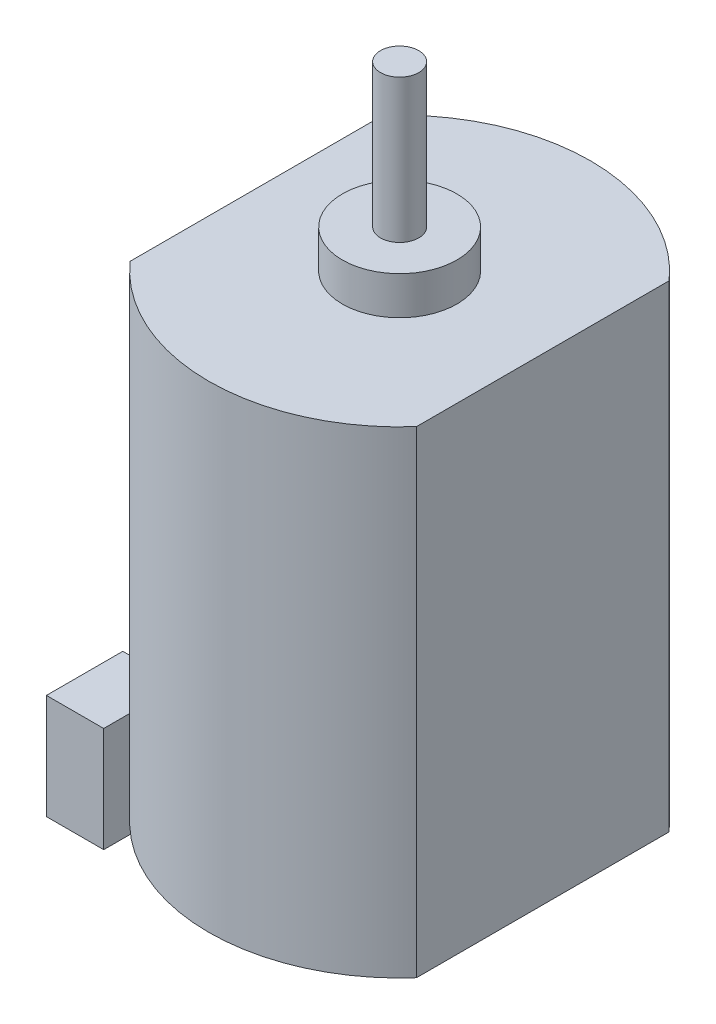
SolidWorks part; units mm, degrees
ref_plane "前视基准面" through (0, 0, 0) normal (0, 0, 1) x (1, 0, 0)
ref_plane "上视基准面" through (0, 0, 0) normal (0, 1, 0) x (1, 0, 0)
ref_plane "右视基准面" through (0, 0, 0) normal (1, 0, 0) x (0, 0, -1)
sketch "草图1" plane through (0, 0, 0) normal (0, 1, 0) x (1, 0, 0)
  circle A0 centre (0, 0) radius 10
  dimension "D1" = 20
extrude "圆柱凸台-拉伸1" add sketch "草图1" along normal blind 25
sketch "草图2" plane through (0, 0, 0) normal (0, -1, 0) x (1, 0, 0)
  line L0 (0, 0) -> (0, 8.2637) construction
  line L2 (-7.5, 10) -> (-7.5, -10)
  line L4 (7.5, 10) -> (7.5, -10)
  line L5 (7.5, 10) -> (10, 10)
  line L6 (-10, 10) -> (-7.5, 10)
  line L7 (-10, 10) -> (-10, -10)
  line L8 (-10, -10) -> (-7.5, -10)
  line L9 (10, 10) -> (10, -10)
  line L10 (7.5, -10) -> (10, -10)
  circle A0 centre (0, 0) radius 10 construction
  dimension "D1" = 15
extrude "2边切除切除-拉伸1" cut sketch "草图2" against normal up to next
sketch "草图3" plane through (0, 25, 0) normal (0, 1, 0) x (1, 0, 0)
  circle A0 centre (0, 0) radius 3
  dimension "D1" = 6
extrude "前转凸台-拉伸2" add sketch "草图3" along normal blind 2
sketch "草图4" plane through (0, 27, 0) normal (0, 1, 0) x (1, 0, 0)
  circle A0 centre (0, 0) radius 1
  dimension "D1" = 2
extrude "前转杆凸台-拉伸3" add sketch "草图4" along normal blind 9.5 from surface at -2 starting at face at (0, 25, 3)
sketch "草图5" plane through (0, 0, 0) normal (0, -1, 0) x (1, 0, 0)
  line L2 (4, 3) -> (4, -3)
  arc A0 (4, 3) -> (4, -3) centre (0, 0) ccw
  dimension "D1" = 10
  dimension "D2" = 4
extrude "后转凸台-拉伸4" add sketch "草图5" along normal blind 27.3 from surface at -25 starting at face at (0, 25, 3)
sketch "草图6" plane through (0, -2.3, 0) normal (0, -1, 0) x (1, 0, 0)
  circle A1 centre (0, 0) radius 1
  dimension "D1" = 2
extrude "后转杆凸台-拉伸5" add sketch "草图6" along normal blind 1
sketch "草图7" plane through (-7.5, 0, 0) normal (-1, 0, 0) x (0, 0, 1)
  line L0 (-8, 3) -> (-8, 4.5)
  line L2 (-8, 3) -> (-8, -1)
  line L3 (-8, -1) -> (-4, -1)
  line L4 (8, 3) -> (8, -1)
  line L5 (0, 0) -> (0, 3) construction
  line L9 (-4, 3) -> (-4, -1)
  line L11 (4, 3) -> (4, -1)
  line L12 (4, -1) -> (8, -1)
  line L13 (-8, 4.5) -> (-4, 4.5)
  line L14 (-4, 4.5) -> (-4, 3)
  line L15 (4, 3) -> (4, 4.5)
  line L16 (4, 4.5) -> (8, 4.5)
  line L17 (8, 4.5) -> (8, 3)
  dimension "D1" = 16
  dimension "D2" = 4
  dimension "D4" = 4
  dimension "D5" = 1.5
  dimension "D6" = 1.5
extrude "引线凸台-拉伸6" add sketch "草图7" along normal blind 3
